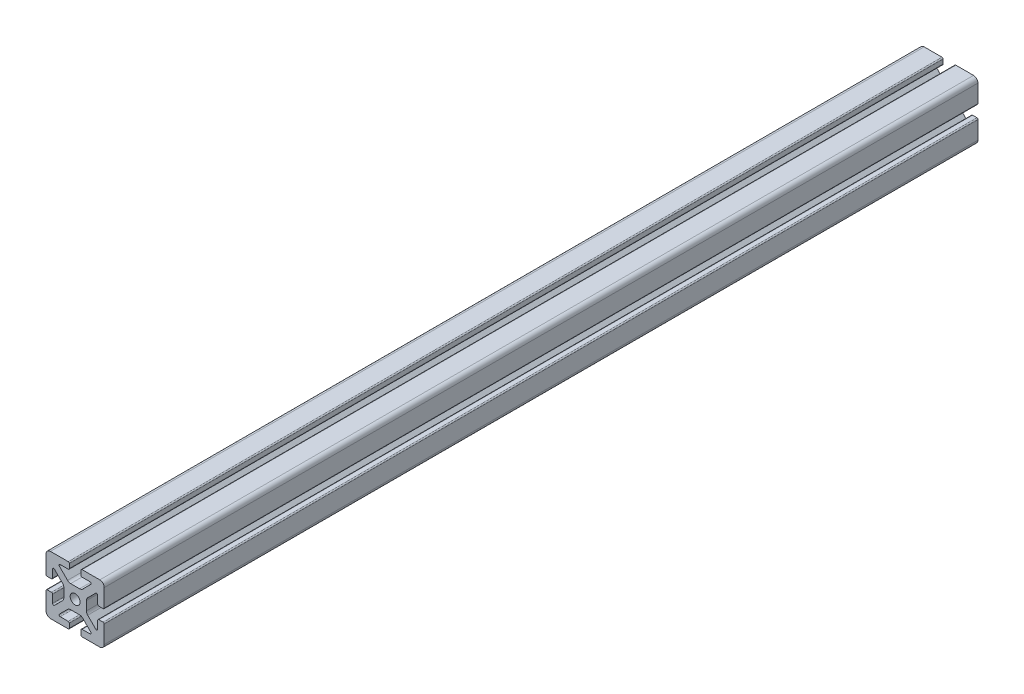
SolidWorks part; units mm, degrees
ref_plane "Front Plane" through (0, 0, 0) normal (0, 0, 1) x (1, 0, 0)
ref_plane "Top Plane" through (0, 0, 0) normal (0, 1, 0) x (1, 0, 0)
ref_plane "Right Plane" through (0, 0, 0) normal (1, 0, 0) x (0, 0, -1)
sketch "Sketch1" plane through (0, 0, 0) normal (0, 0, 1) x (1, 0, 0)
  line L2 (-20, 16.952) -> (-20, 4.7625)
  line L3 (-16.952, 20) -> (-4.7625, 20)
  line L4 (-4.0005, 19.238) -> (-4.0005, 16.2662)
  line L5 (-4.7625, 15.5042) -> (-10.2235, 15.5042)
  line L6 (-10.7623, 14.2034) -> (-5.194, 8.6351)
  line L7 (-14.2034, 10.7623) -> (-8.6351, 5.194)
  line L8 (-15.5042, 10.2235) -> (-15.5042, 4.7625)
  line L9 (-16.2662, 4.0005) -> (-19.238, 4.0005)
  line L11 (-3.0746, 7.7572) -> (3.0746, 7.7572)
  line L12 (-7.7572, 3.0746) -> (-7.7572, -3.0746)
  line L13 (16.2662, 4.0005) -> (19.238, 4.0005)
  line L14 (15.5042, 10.2235) -> (15.5042, 4.7625)
  line L15 (20, 16.952) -> (20, 4.7625)
  line L16 (16.952, 20) -> (4.7625, 20)
  line L17 (4.0005, 19.238) -> (4.0005, 16.2662)
  line L18 (4.7625, 15.5042) -> (10.2235, 15.5042)
  line L19 (7.7572, 3.0746) -> (7.7572, -3.0746)
  line L20 (10.7623, 14.2034) -> (5.194, 8.6351)
  line L21 (14.2034, 10.7623) -> (8.6351, 5.194)
  line L22 (-16.2662, -4.0005) -> (-19.238, -4.0005)
  line L23 (-15.5042, -10.2235) -> (-15.5042, -4.7625)
  line L24 (-14.2034, -10.7623) -> (-8.6351, -5.194)
  line L25 (-10.7623, -14.2034) -> (-5.194, -8.6351)
  line L26 (-4.7625, -15.5042) -> (-10.2235, -15.5042)
  line L27 (-4.0005, -19.238) -> (-4.0005, -16.2662)
  line L28 (-16.952, -20) -> (-4.7625, -20)
  line L29 (-20, -16.952) -> (-20, -4.7625)
  line L30 (20, -16.952) -> (20, -4.7625)
  line L31 (16.952, -20) -> (4.7625, -20)
  line L32 (4.0005, -19.238) -> (4.0005, -16.2662)
  line L33 (4.7625, -15.5042) -> (10.2235, -15.5042)
  line L34 (10.7623, -14.2034) -> (5.194, -8.6351)
  line L35 (14.2034, -10.7623) -> (8.6351, -5.194)
  line L36 (15.5042, -10.2235) -> (15.5042, -4.7625)
  line L37 (16.2662, -4.0005) -> (19.238, -4.0005)
  line L38 (-3.0746, -7.7572) -> (3.0746, -7.7572)
  circle A0 centre (0, 0) radius 3.4036
  arc A1 (-20, 16.952) -> (-16.952, 20) centre (-16.952, 16.952) cw
  arc A2 (-14.2034, 10.7623) -> (-15.5042, 10.2235) centre (-14.7422, 10.2235) ccw
  arc A3 (-10.2235, 15.5042) -> (-10.7623, 14.2034) centre (-10.2235, 14.7422) ccw
  arc A4 (-4.7625, 20) -> (-4.0005, 19.238) centre (-4.7625, 19.238) cw
  arc A5 (-20, 4.7625) -> (-19.238, 4.0005) centre (-19.238, 4.7625) ccw
  arc A6 (-15.5042, 4.7625) -> (-16.2662, 4.0005) centre (-16.2662, 4.7625) cw
  arc A7 (-4.0005, 16.2662) -> (-4.7625, 15.5042) centre (-4.7625, 16.2662) cw
  arc A8 (-3.0746, 7.7572) -> (-5.194, 8.6351) centre (-3.0746, 10.7544) cw
  arc A9 (-7.7572, 3.0746) -> (-8.6351, 5.194) centre (-10.7544, 3.0746) ccw
  arc A10 (15.5042, 4.7625) -> (16.2662, 4.0005) centre (16.2662, 4.7625) ccw
  arc A11 (20, 4.7625) -> (19.238, 4.0005) centre (19.238, 4.7625) cw
  arc A12 (20, 16.952) -> (16.952, 20) centre (16.952, 16.952) ccw
  arc A13 (4.7625, 20) -> (4.0005, 19.238) centre (4.7625, 19.238) ccw
  arc A14 (4.0005, 16.2662) -> (4.7625, 15.5042) centre (4.7625, 16.2662) ccw
  arc A15 (3.0746, 7.7572) -> (5.194, 8.6351) centre (3.0746, 10.7544) ccw
  arc A16 (7.7572, 3.0746) -> (8.6351, 5.194) centre (10.7544, 3.0746) cw
  arc A17 (14.2034, 10.7623) -> (15.5042, 10.2235) centre (14.7422, 10.2235) cw
  arc A18 (10.2235, 15.5042) -> (10.7623, 14.2034) centre (10.2235, 14.7422) cw
  arc A19 (-7.7572, -3.0746) -> (-8.6351, -5.194) centre (-10.7544, -3.0746) cw
  arc A20 (-3.0746, -7.7572) -> (-5.194, -8.6351) centre (-3.0746, -10.7544) ccw
  arc A21 (-4.0005, -16.2662) -> (-4.7625, -15.5042) centre (-4.7625, -16.2662) ccw
  arc A22 (-15.5042, -4.7625) -> (-16.2662, -4.0005) centre (-16.2662, -4.7625) ccw
  arc A23 (-20, -4.7625) -> (-19.238, -4.0005) centre (-19.238, -4.7625) cw
  arc A24 (-4.7625, -20) -> (-4.0005, -19.238) centre (-4.7625, -19.238) ccw
  arc A25 (-10.2235, -15.5042) -> (-10.7623, -14.2034) centre (-10.2235, -14.7422) cw
  arc A26 (-14.2034, -10.7623) -> (-15.5042, -10.2235) centre (-14.7422, -10.2235) cw
  arc A27 (-20, -16.952) -> (-16.952, -20) centre (-16.952, -16.952) ccw
  arc A28 (20, -16.952) -> (16.952, -20) centre (16.952, -16.952) cw
  arc A29 (14.2034, -10.7623) -> (15.5042, -10.2235) centre (14.7422, -10.2235) ccw
  arc A30 (10.2235, -15.5042) -> (10.7623, -14.2034) centre (10.2235, -14.7422) ccw
  arc A31 (4.7625, -20) -> (4.0005, -19.238) centre (4.7625, -19.238) cw
  arc A32 (20, -4.7625) -> (19.238, -4.0005) centre (19.238, -4.7625) ccw
  arc A33 (15.5042, -4.7625) -> (16.2662, -4.0005) centre (16.2662, -4.7625) cw
  arc A34 (4.0005, -16.2662) -> (4.7625, -15.5042) centre (4.7625, -16.2662) cw
  arc A35 (3.0746, -7.7572) -> (5.194, -8.6351) centre (3.0746, -10.7544) cw
  arc A36 (7.7572, -3.0746) -> (8.6351, -5.194) centre (10.7544, -3.0746) ccw
extrude "Boss-Extrude1" add sketch "Sketch1" along normal mid plane 600
